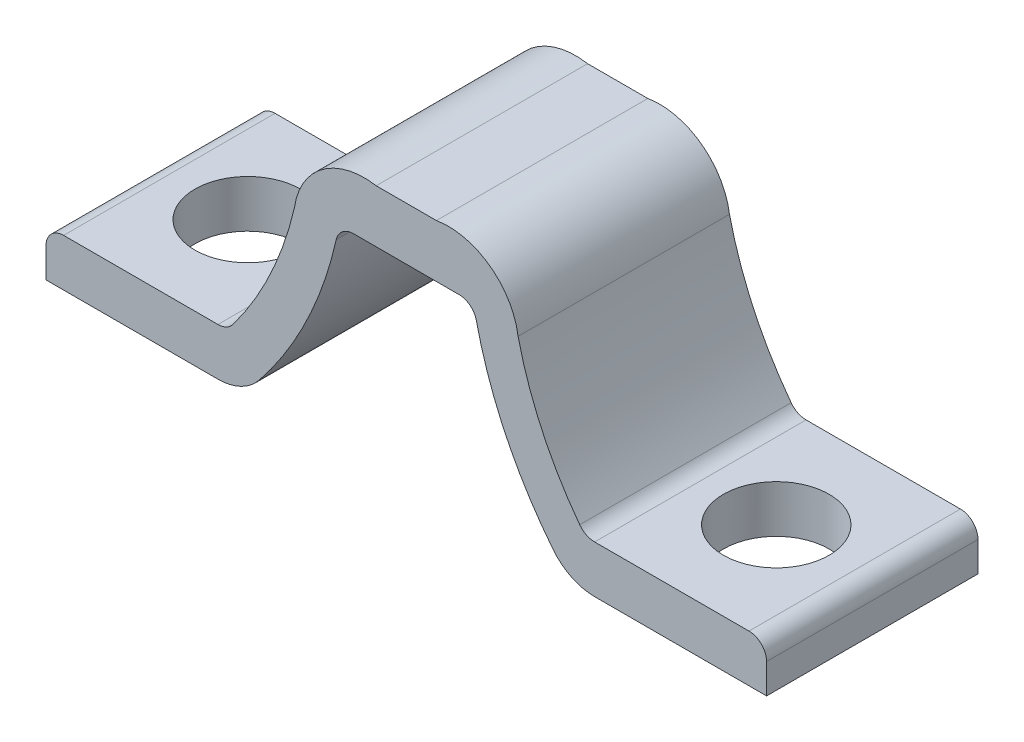
SolidWorks part; units mm, degrees
material "201 Annealed Stainless Steel (SS)"
ref_plane "Front Plane" through (0, 0, 0) normal (0, 0, 1) x (1, 0, 0)
ref_plane "Top Plane" through (0, 0, 0) normal (0, 1, 0) x (1, 0, 0)
ref_plane "Right Plane" through (0, 0, 0) normal (1, 0, 0) x (0, 0, -1)
sketch "Sketch1" plane through (0, 0, 0) normal (0, 0, 1) x (1, 0, 0)
  line L0 (1.905, 6.985) -> (-1.905, 6.985)
  line L1 (-12.9859, 0) -> (-6.7887, 0)
  line L2 (-12.9859, 0) -> (-12.9859, 1.0732)
  line L3 (-12.3509, 1.7082) -> (-6.7887, 1.7082)
  line L4 (12.3509, 1.7082) -> (6.7887, 1.7082)
  line L5 (12.9859, 0) -> (12.9859, 1.0732)
  line L6 (-1.0854, 8.89) -> (1.0854, 8.89)
  line L17 (12.9859, 0) -> (6.7887, 0)
  arc A0 (-6.2507, 1.9768) -> (-4.0293, 6.745) centre (-16.4025, 9.6077) ccw
  arc A1 (-1.0854, 8.89) -> (-4.0293, 6.745) centre (-1.5148, 6.3865) ccw
  arc A2 (-12.9859, 1.0732) -> (-12.3509, 1.7082) centre (-12.3509, 1.0732) cw
  arc A3 (-6.7887, 1.7082) -> (-6.2507, 1.9768) centre (-6.7887, 2.3811) ccw
  arc A4 (-6.7887, 0) -> (-5.302, 0.7139) centre (-6.7887, 1.905) ccw
  arc A5 (-5.302, 0.7139) -> (-2.5246, 6.4892) centre (-16.4025, 9.6077) ccw
  arc A6 (-1.905, 6.985) -> (-2.5246, 6.4892) centre (-1.905, 6.35) ccw
  arc A9 (1.905, 6.985) -> (2.5246, 6.4892) centre (1.905, 6.35) cw
  arc A10 (5.302, 0.7139) -> (2.5246, 6.4892) centre (16.4025, 9.6077) cw
  arc A11 (6.7887, 0) -> (5.302, 0.7139) centre (6.7887, 1.905) cw
  arc A19 (6.7887, 1.7082) -> (6.2507, 1.9768) centre (6.7887, 2.3811) cw
  arc A20 (12.9859, 1.0732) -> (12.3509, 1.7082) centre (12.3509, 1.0732) ccw
  arc A21 (1.0854, 8.89) -> (4.0293, 6.745) centre (1.5148, 6.3865) cw
  arc A22 (6.2507, 1.9768) -> (4.0293, 6.745) centre (16.4025, 9.6077) cw
  point P0 (6.7887, 1.7082)
  point P1 (-3.6192, 8.255)
  point P21 (0, 6.985)
  point P67 (3.6192, 8.255)
  dimension "D2" = 8.89
  dimension "D4" = 1.524
  dimension "D7" = 0.635
  dimension "D3" = 1.7082
  dimension "D1" = 0.635
  dimension "D5" = 1.905
extrude "Boss-Extrude1" add sketch "Sketch1" along normal blind 7.62
sketch "Sketch2" plane through (0, 1.7082, 0) normal (0, 1, 0) x (1, 0, 0)
  line L0 (9.525, 0) -> (9.525, -7.62) construction
  line L2 (0, -7.62) -> (0, 0) construction
  line L3 (-9.525, 0) -> (-9.525, -7.62) construction
  line L6 (-1.0854, -7.62) -> (1.0854, -7.62) construction
  line L7 (-9.525, -3.81) -> (9.525, -3.81)
  circle A0 centre (9.525, -3.81) radius 1.905
  circle A1 centre (-9.525, -3.81) radius 1.905
  point P4 (0, -3.81)
  dimension "D1" = 3.81
  dimension "D2" = 19.05
extrude "Cut-Extrude1" cut sketch "Sketch2" against normal blind 5.08
sketch "Sketch3" plane through (0, 0, 0) normal (0, 0, 1) x (1, 0, 0)
  line L0 (6.7887, 0) -> (-6.7887, 0) construction
  circle A0 centre (0, 3.175) radius 3.175
  dimension "D1" = 6.35
